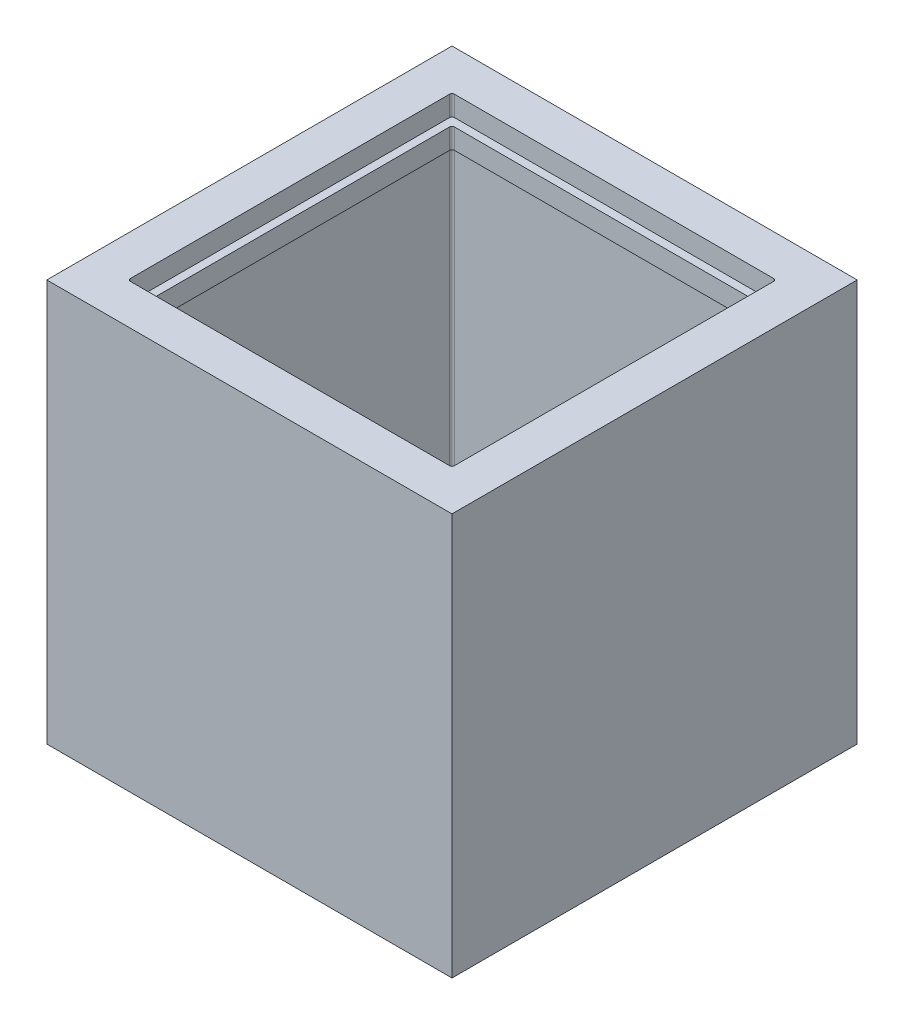
SolidWorks part; units mm, degrees
ref_plane "Front Plane" through (0, 0, 0) normal (0, 0, 1) x (1, 0, 0)
ref_plane "Top Plane" through (0, 0, 0) normal (0, 1, 0) x (1, 0, 0)
ref_plane "Right Plane" through (0, 0, 0) normal (1, 0, 0) x (0, 0, -1)
sketch "Sketch1" plane through (0, 0, 0) normal (0, 0, 1) x (1, 0, 0)
  line L1 (-63.5, -63.5) -> (63.5, -63.5)
  line L2 (-63.5, -63.5) -> (-63.5, 63.5)
  line L3 (-63.5, 63.5) -> (63.5, 63.5)
  line L4 (63.5, -63.5) -> (63.5, 63.5)
  line L5 (-63.5, -63.5) -> (63.5, 63.5) construction
  line L6 (-63.5, 63.5) -> (63.5, -63.5) construction
  point P0 (0, 0)
  dimension "D1" = 127
  dimension "D2" = 127
extrude "Boss-Extrude1" add sketch "Sketch1" along normal blind 127
sketch "Sketch2" plane through (0, 63.5, 0) normal (0, 1, 0) x (1, 0, 0)
  line L16 (-48.26, -15.24) -> (-48.26, -111.76)
  line L17 (-48.26, -111.76) -> (48.26, -111.76)
  line L18 (48.26, -111.76) -> (48.26, -15.24)
  line L19 (48.26, -15.24) -> (-48.26, -15.24)
  line L20 (-48.26, -15.24) -> (-48.26, -111.76)
  line L21 (-48.26, -111.76) -> (48.26, -111.76)
  line L22 (48.26, -111.76) -> (48.26, -15.24)
  line L23 (48.26, -15.24) -> (-48.26, -15.24)
  dimension "D1" = 15.24
extrude "Cut-Extrude1" cut sketch "Sketch2" against normal blind 118.11
sketch "Sketch3" plane through (0, 63.5, 0) normal (0, 1, 0) x (1, 0, 0)
  line L1 (-48.26, -15.24) -> (48.26, -15.24)
  line L2 (-48.26, -15.24) -> (-48.26, -111.76)
  line L3 (-48.26, -111.76) -> (48.26, -111.76)
  line L4 (48.26, -15.24) -> (48.26, -111.76)
  line L14 (-50.8, -114.3) -> (50.8, -114.3)
  line L15 (50.8, -114.3) -> (50.8, -12.7)
  line L16 (-50.8, -12.7) -> (-50.8, -114.3)
  line L17 (50.8, -12.7) -> (-50.8, -12.7)
  line L18 (-50.8, -114.3) -> (50.8, -114.3)
  line L19 (50.8, -114.3) -> (50.8, -12.7)
  line L20 (-50.8, -12.7) -> (-50.8, -114.3)
  line L21 (50.8, -12.7) -> (-50.8, -12.7)
  dimension "D1" = 2.54
extrude "Cut-Extrude2" cut sketch "Sketch3" against normal blind 6.35
sketch "Sketch5" plane through (0, 0, 15.24) normal (0, 0, 1) x (1, 0, 0)
  line L0 (-48.26, -54.61) -> (-48.26, 57.15) construction
  line L1 (-48.26, 50.8) -> (48.26, 50.8)
  line L2 (-48.26, 50.8) -> (-48.26, -54.61)
  line L3 (-48.26, -54.61) -> (48.26, -54.61)
  line L4 (48.26, 50.8) -> (48.26, -54.61)
  line L5 (48.26, -54.61) -> (-48.26, -54.61) construction
  line L6 (48.26, -54.61) -> (48.26, 57.15) construction
  line L7 (50.8, 57.15) -> (-50.8, 57.15) construction
  dimension "D1" = 6.35
extrude "Cut-Extrude3" cut sketch "Sketch5" against normal blind 6.35
ref_plane "Plane1" through (0, 0, 63.5) normal (0, 0, -1) x (-1, 0, 0)
mirror "Mirror1" about plane through (0, 0, 63.5) normal (0, 0, -1) of "Cut-Extrude3"
sketch "Sketch6" plane through (48.26, 0, 0) normal (-1, 0, 0) x (0, 0, 1)
  line L0 (118.11, -54.61) -> (118.11, 50.8) construction
  line L1 (8.89, -54.61) -> (118.11, -54.61)
  line L2 (8.89, -54.61) -> (8.89, 50.8)
  line L3 (8.89, 50.8) -> (118.11, 50.8)
  line L4 (118.11, -54.61) -> (118.11, 50.8)
  line L5 (8.89, 50.8) -> (15.24, 50.8) construction
  dimension "D1" = 0
extrude "Cut-Extrude4" cut sketch "Sketch6" against normal blind 6.35
mirror "Mirror2" about plane through (0, 0, 0) normal (1, 0, 0) of "Cut-Extrude4"
chamfer "Chamfer1" distance 1.016 angle 45 4 edges at (-63.5, -63.5, 63.5) (0, -63.5, 0) (63.5, -63.5, 63.5) (0, -63.5, 127)
fillet "Fillet1" [suppressed] radius 0.762
fillet "Fillet2" radius 0.762 4 edges at (54.61, -1.905, 118.11) (-54.61, -1.905, 8.89) (-54.61, -1.905, 118.11) (54.61, -1.905, 8.89)
fillet "Fillet3" radius 0.762 8 edges at (50.8, 60.325, 114.3) (48.26, 53.975, 111.76) (50.8, 60.325, 12.7) (48.26, 53.975, 15.24) (-50.8, 60.325, 114.3) (-48.26, 53.975, 111.76) (-48.26, 53.975, 15.24) (-50.8, 60.325, 12.7)
fillet "Fillet4" radius 0.762 8 edges at (-54.3868, 50.8, 117.8868) (0, 50.8, 118.11) (54.3868, 50.8, 117.8868) (54.61, 50.8, 63.5) (54.3868, 50.8, 9.1132) (0, 50.8, 8.89) (-54.3868, 50.8, 9.1132) (-54.61, 50.8, 63.5)
